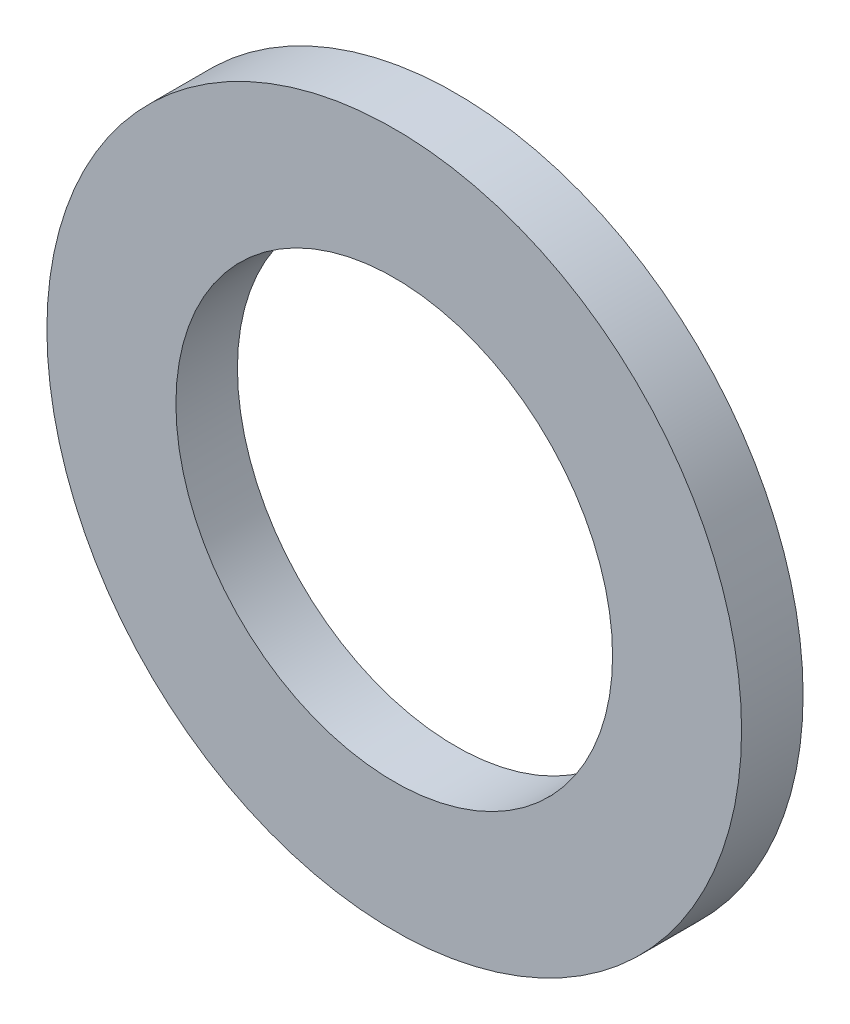
SolidWorks part; units mm, degrees
ref_plane "Front Plane" through (0, 0, 0) normal (0, 0, 1) x (1, 0, 0)
ref_plane "Top Plane" through (0, 0, 0) normal (0, 1, 0) x (1, 0, 0)
ref_plane "Right Plane" through (0, 0, 0) normal (1, 0, 0) x (0, 0, -1)
sketch "Sketch1" plane through (0, 0, 0) normal (0, 0, 1) x (1, 0, 0)
  circle A5 centre (0, 0) radius 110
  circle A6 centre (0, 0) radius 175
  dimension "D1" = 220
  dimension "D2" = 350
extrude "Boss-Extrude1" add sketch "Sketch1" along normal blind 31
